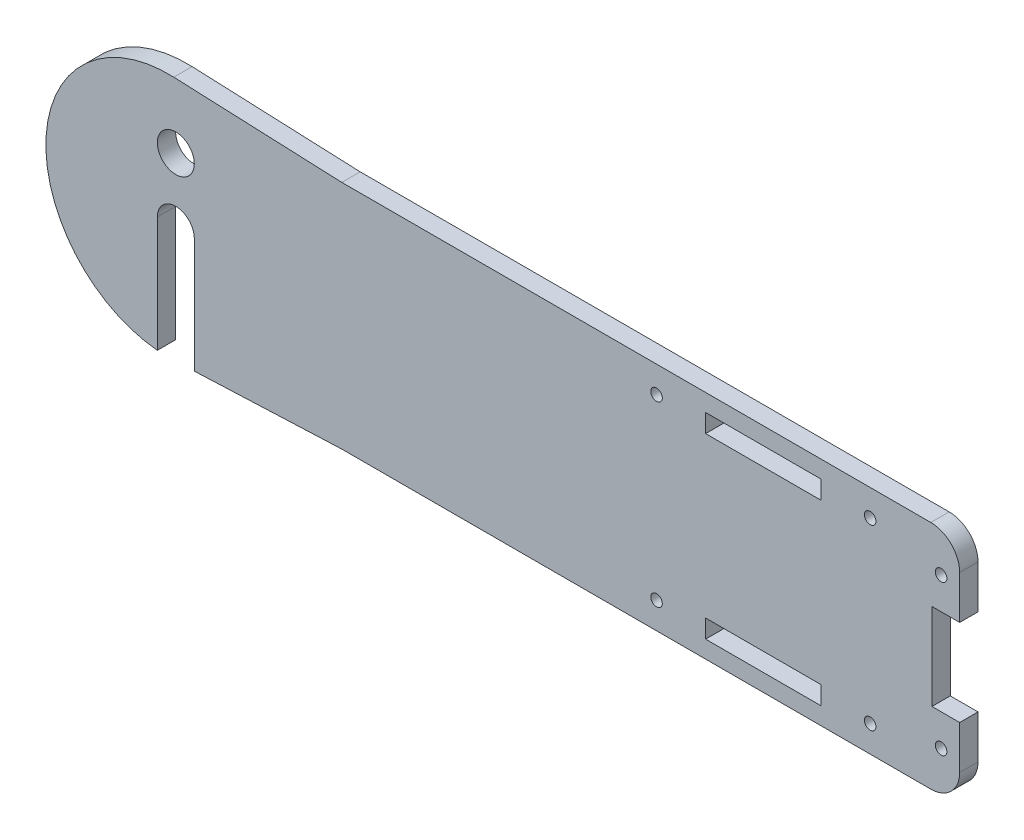
SolidWorks part; units mm, degrees
ref_plane "Front Plane" through (0, 0, 0) normal (0, 0, 1) x (1, 0, 0)
ref_plane "Top Plane" through (0, 0, 0) normal (0, 1, 0) x (1, 0, 0)
ref_plane "Right Plane" through (0, 0, 0) normal (1, 0, 0) x (0, 0, -1)
sketch "Sketch1" plane through (0, 0, 0) normal (0, 0, 1) x (1, 0, 0)
  line L0 (-111.1019, 21.231) -> (-82, 20)
  line L1 (-82, 20) -> (25, 20)
  line L2 (25, 20) -> (25, -20)
  line L3 (25, -20) -> (-82, -20)
  line L4 (-82, -20) -> (-111.1019, -21.231)
  arc A0 (-111.1019, 21.231) -> (-111.1019, -21.231) centre (-112, 0) ccw
  dimension "D1" = 42.5
  dimension "D3" = 20
  dimension "D2" = 20
  dimension "D4" = 20
  dimension "D5" = 25
  dimension "D6" = 112
  dimension "D7" = 30
  dimension "D8" = 30
extrude "Boss-Extrude1" add sketch "Sketch1" against normal blind 3.175
sketch "Sketch3" plane through (0, 0, 0) normal (0, 0, 1) x (1, 0, 0)
  line L0 (0, 0) -> (-133.25, 0) construction
  arc A1 (-111.1019, 21.231) -> (-111.1019, -21.231) centre (-112, 0) ccw construction
  circle A2 centre (-110.75, 10) radius 3.2
  dimension "D1" = 10
  dimension "D2" = 6.4
  dimension "D3" = 22.5
extrude "Cut-Extrude1" cut sketch "Sketch3" against normal through all both and the other way through all
sketch "Sketch6" plane through (0, 0, 0) normal (0, 0, 1) x (1, 0, 0)
  line L1 (-19, 17) -> (1, 17)
  line L2 (-19, 17) -> (-19, 13.825)
  line L3 (-19, 13.825) -> (1, 13.825)
  line L4 (1, 17) -> (1, 13.825)
  circle A0 centre (9.5, 15.4125) radius 1
  circle A1 centre (-27.5, 15.4125) radius 1
  point P4 (-9, 13.825)
  point P8 (-9, 17)
  point P9 (1, 15.4125)
  point P12 (-19, 15.4125)
  dimension "D5" = 2
  dimension "D6" = 18.5
  dimension "D7" = 0
  dimension "D8" = 2
  dimension "D9" = 0
  dimension "D10" = 18.5
  dimension "D1" = 3.175
  dimension "D2" = 17
  dimension "D3" = 20
  dimension "D4" = 9
extrude "Cut-Extrude4" cut sketch "Sketch6" against normal through all both and the other way through all
ref_plane "Plane1" through (0, 0, 0) normal (0, 1, 0) x (1, 0, 0)
mirror "Mirror1" about plane through (0, 0, 0) normal (0, 1, 0) of "Cut-Extrude4"
sketch "Sketch7" plane through (0, 0, 0) normal (0, 0, 1) x (1, 0, 0)
  line L0 (25, -20) -> (25, 20) construction
  line L1 (25, 7.5) -> (20.2, 7.5)
  line L2 (25, 7.5) -> (25, -7.5)
  line L3 (25, -7.5) -> (20.2, -7.5)
  line L4 (20.2, 7.5) -> (20.2, -7.5)
  circle A0 centre (21.7875, 13) radius 1
  circle A1 centre (21.7875, -13) radius 1
  point P6 (20.2, 0)
  dimension "D4" = 2
  dimension "D5" = 1.5875
  dimension "D6" = 13
  dimension "D7" = 2
  dimension "D8" = 13
  dimension "D9" = 1.5875
  dimension "D1" = 4.8
  dimension "D2" = 0
  dimension "D3" = 15
extrude "Cut-Extrude5" cut sketch "Sketch7" against normal through all both and the other way through all
fillet "Fillet2" radius 5 1 edges at (25, 20, -1.5875)
fillet "Fillet3" radius 5 1 edges at (25, -20, -1.5875)
sketch "Sketch8" plane through (0, 0, 0) normal (0, 0, 1) x (1, 0, 0)
  line L0 (-107.55, -1.1603) -> (-107.55, -21.0808)
  line L1 (-111.1019, -21.231) -> (-82, -20) construction
  line L2 (-113.95, -1.1603) -> (-113.95, -21.1603)
  arc A0 (-111.1019, 21.231) -> (-111.1019, -21.231) centre (-112, 0) ccw construction
  arc A1 (-107.55, -1.1603) -> (-113.95, -1.1603) centre (-110.75, -1.1603) ccw
  circle A2 centre (-110.75, 10) radius 3.2 construction
  dimension "D2" = 3.2
  dimension "D3" = 20
  dimension "D1" = 6.4
extrude "Cut-Extrude6" cut sketch "Sketch8" against normal through all and the other way through all
